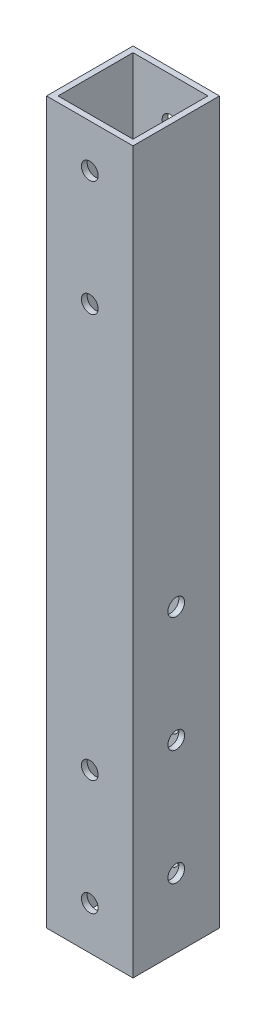
SolidWorks part; units mm, degrees
material "Thornel Mat VMA"
ref_plane "前视基准面" through (0, 0, 0) normal (0, 0, 1) x (1, 0, 0)
ref_plane "上视基准面" through (0, 0, 0) normal (0, 1, 0) x (1, 0, 0)
ref_plane "右视基准面" through (0, 0, 0) normal (1, 0, 0) x (0, 0, -1)
sketch "草图1" plane through (0, 0, 0) normal (0, 1, 0) x (1, 0, 0)
  line L1 (-7.5, -7.5) -> (7.5, -7.5)
  line L2 (-7.5, -7.5) -> (-7.5, 7.5)
  line L3 (-7.5, 7.5) -> (7.5, 7.5)
  line L4 (7.5, -7.5) -> (7.5, 7.5)
  line L5 (-7.5, -7.5) -> (7.5, 7.5) construction
  line L6 (-7.5, 7.5) -> (7.5, -7.5) construction
  point P0 (0, 0)
  dimension "D1" = 15
  dimension "D2" = 15
extrude "拉伸-薄壁1" add sketch "草图1" along normal blind 125 thin thin type one direction reverse wall 1
sketch "草图2" plane through (0, 0, 7.5) normal (0, 0, 1) x (1, 0, 0)
  line L0 (0, 0) -> (0, 125) construction
  line L1 (-7.5, 125) -> (7.5, 125) construction
  line L2 (-7.5, 0) -> (7.5, 0) construction
  line L3 (-1000, 62.5) -> (49000, 62.5) construction
  circle A0 centre (0, 7.5) radius 1.45
  circle A1 centre (0, 27.5) radius 1.45
  circle A2 centre (0, 97.5) radius 1.45
  circle A3 centre (0, 117.5) radius 1.45
  point P14 (0, 62.5)
  dimension "D1" = 2.9
  dimension "D2" = 7.5
  dimension "D3" = 20
extrude "切除-拉伸1" cut sketch "草图2" against normal through all
sketch "草图3" plane through (7.5, 0, 0) normal (1, 0, 0) x (0, 0, -1)
  line L0 (0, 0) -> (0, 125) construction
  line L1 (-7.5, 125) -> (7.5, 125) construction
  line L2 (-7.5, 0) -> (7.5, 0) construction
  circle A0 centre (0, 32) radius 1.45
  circle A1 centre (0, 12) radius 1.45
  circle A2 centre (0, 52) radius 1.45
  dimension "D1" = 2.9
  dimension "D2" = 20
  dimension "D3" = 20
  dimension "D4" = 12
extrude "切除-拉伸2" cut sketch "草图3" against normal through all
